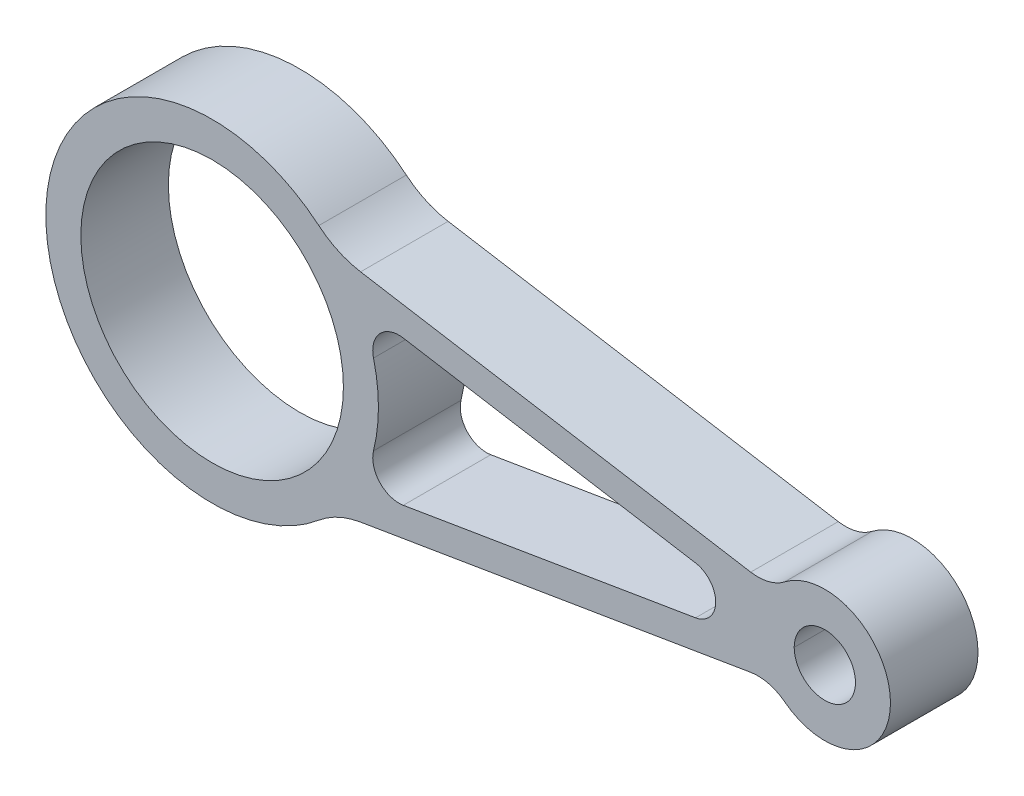
SolidWorks part; units mm, degrees
material "Plain Carbon Steel"
ref_plane "Front Plane" through (0, 0, 0) normal (0, 0, 1) x (1, 0, 0)
ref_plane "Top Plane" through (0, 0, 0) normal (0, 1, 0) x (1, 0, 0)
ref_plane "Right Plane" through (0, 0, 0) normal (1, 0, 0) x (0, 0, -1)
sketch "Sketch1" plane through (0, 0, 0) normal (0, 0, 1) x (1, 0, 0)
  line L0 (-37.4661, 0) -> (319.0657, 0) construction
  line L1 (27.9355, 25.7606) -> (128.0638, 9.0844)
  line L2 (27.9355, -25.7606) -> (128.0638, -9.0844)
  circle A0 centre (0, 0) radius 30
  circle A1 centre (140, 0) radius 7
  arc A4 (27.9355, 25.7606) -> (27.9355, -25.7606) centre (0, 0) ccw
  arc A5 (128.0638, -9.0844) -> (128.0638, 9.0844) centre (140, 0) ccw
  circle A6 centre (0, 0) radius 38 construction
  circle A7 centre (140, 0) radius 15 construction
  dimension "D1" = 60
  dimension "D2" = 14
  dimension "D3" = 140
  dimension "D4" = 8
  dimension "D5" = 8
extrude "Boss-Extrude1" add sketch "Sketch1" along normal mid plane 20
fillet "Fillet1" radius 20 2 edges at (27.9355, -25.7606, 0) (27.9355, 25.7606, 0)
fillet "Fillet2" radius 10 2 edges at (128.0638, -9.0844, 0) (128.0638, 9.0844, 0)
sketch "Sketch3" plane through (0, 0, 10) normal (0, 0, 1) x (1, 0, 0)
  line L0 (43.6824, 16.5485) -> (110.4688, 5.4253)
  line L1 (110.4688, -5.4253) -> (43.6824, -16.5485)
  line L2 (123.0688, 9.9163) -> (33.9231, 24.7634) construction
  line L3 (0, 0) -> (167.4868, 0) construction
  circle A2 centre (0, 0) radius 38
  arc A3 (36.8744, -9.1804) -> (36.8744, 9.1804) centre (0, 0) ccw
  arc A4 (110.4688, 5.4253) -> (110.4688, -5.4253) centre (109.5652, 0) cw
  arc A5 (43.6824, -16.5485) -> (36.8744, -9.1804) centre (42.6966, -10.63) cw
  arc A6 (43.6824, 16.5485) -> (36.8744, 9.1804) centre (42.6966, 10.63) ccw
  dimension "D2" = 5.5
  dimension "D3" = 6
  dimension "D4" = 6.5
  dimension "D1" = 8
extrude "Cut-Extrude1" cut sketch "Sketch3" against normal through all
split line "Split Line1"
